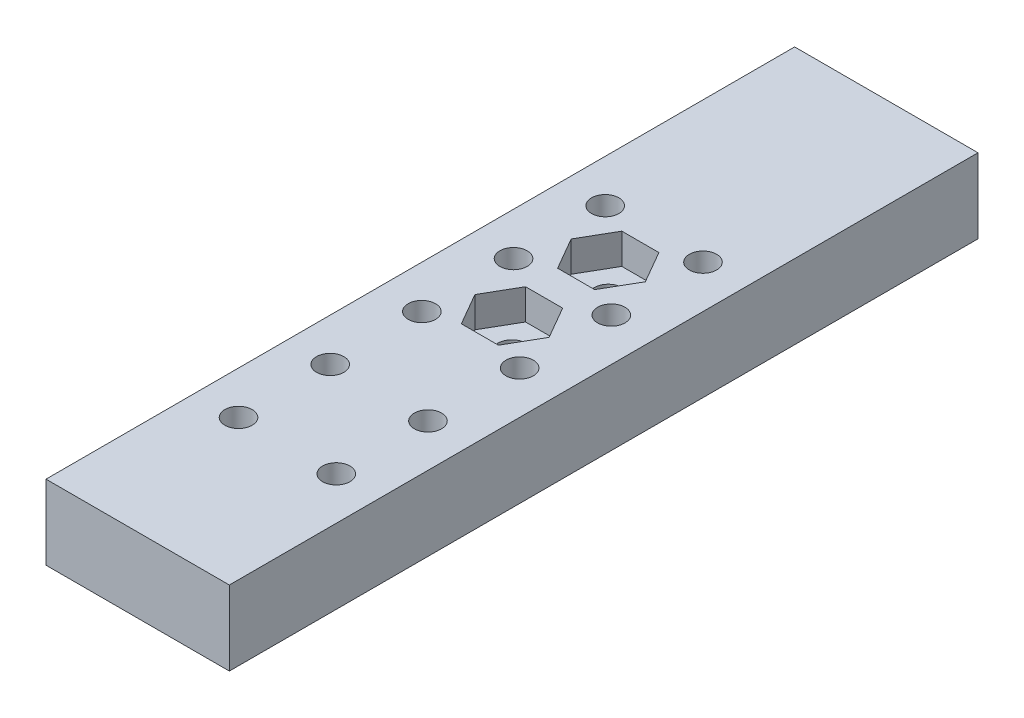
SolidWorks part; units mm, degrees
ref_plane "Front Plane" through (0, 0, 0) normal (0, 0, 1) x (1, 0, 0)
ref_plane "Top Plane" through (0, 0, 0) normal (0, 1, 0) x (1, 0, 0)
ref_plane "Right Plane" through (0, 0, 0) normal (1, 0, 0) x (0, 0, -1)
sketch "Sketch1" plane through (0, 0, 0) normal (0, 1, 0) x (1, 0, 0)
  line L0 (-8, 23.25) -> (8, 23.25) construction
  line L1 (8, 23.25) -> (0, 23.25) construction
  line L2 (0, 61.25) -> (0, -61.25) construction
  line L3 (-15, -61.25) -> (15, -61.25)
  line L4 (-15, -61.25) -> (-15, 61.25)
  line L5 (-15, 61.25) -> (15, 61.25)
  line L6 (15, -61.25) -> (15, 61.25)
  line L7 (-15, -61.25) -> (15, 61.25) construction
  line L8 (-15, 61.25) -> (15, -61.25) construction
  line L9 (-8, 23.25) -> (8, 8.25) construction
  circle A0 centre (-8, 23.25) radius 2.2349
  circle A1 centre (8, 23.25) radius 2.2349
  circle A2 centre (8, 8.25) radius 2.2349
  circle A3 centre (8, -6.75) radius 2.2349
  circle A4 centre (8, -21.75) radius 2.2349
  circle A5 centre (8, -36.75) radius 2.2349
  circle A6 centre (-8, 8.25) radius 2.2349
  circle A7 centre (-8, -6.75) radius 2.2349
  circle A8 centre (-8, -21.75) radius 2.2349
  circle A9 centre (-8, -36.75) radius 2.2349
  circle A10 centre (0, 15.75) radius 2.3
  circle A11 centre (0, 0) radius 2.3
  point P5 (0, 0)
  dimension "D3" = 4.6
  dimension "D4" = 4.6
  dimension "D1" = 122.5
  dimension "D2" = 30
extrude "Boss-Extrude1" add sketch "Sketch1" along normal blind 13
sketch "Sketch2" plane through (0, 13, 0) normal (0, 1, 0) x (1, 0, 0)
  line L0 (8, 8.25) -> (-8, 23.25) construction
  line L2 (6.0669, 0) -> (3.0335, 5.2541)
  line L3 (3.0335, 5.2541) -> (-3.0335, 5.2541)
  line L4 (-3.0335, 5.2541) -> (-6.0669, 0)
  line L5 (-6.0669, 0) -> (-3.0335, -5.2541)
  line L6 (-3.0335, -5.2541) -> (3.0335, -5.2541)
  line L7 (3.0335, -5.2541) -> (6.0669, 0)
  line L8 (6.0669, 15.75) -> (3.0335, 21.0041)
  line L9 (3.0335, 21.0041) -> (-3.0335, 21.0041)
  line L10 (-3.0335, 21.0041) -> (-6.0669, 15.75)
  line L11 (-6.0669, 15.75) -> (-3.0335, 10.4959)
  line L12 (-3.0335, 10.4959) -> (3.0335, 10.4959)
  line L13 (3.0335, 10.4959) -> (6.0669, 15.75)
  circle A0 centre (0, 0) radius 5.2541 construction
  circle A1 centre (0, 15.75) radius 5.2541 construction
extrude "Cut-Extrude1" cut sketch "Sketch2" against normal blind 5
chamfer "Chamfer1" distance 0.8 angle 45 2 edges at (15, 0, 0) (-15, 0, 0)
sketch "Sketch3" plane through (0, 0, 0) normal (0, -1, 0) x (1, 0, 0)
  circle A0 centre (8, 36.75) radius 4.5
  circle A1 centre (-8, 36.75) radius 4.5
  circle A2 centre (-8, 21.75) radius 4.5
  circle A3 centre (-8, 6.75) radius 4.5
  circle A4 centre (-8, -8.25) radius 4.5
  circle A5 centre (-8, -23.25) radius 4.5
  circle A6 centre (8, 21.75) radius 4.5
  circle A7 centre (8, 6.75) radius 4.5
  circle A8 centre (8, -8.25) radius 4.5
  circle A9 centre (8, -23.25) radius 4.5
  dimension "D1" = 9
  dimension "D2" = 2
  dimension "D3" = 5
extrude "Cut-Extrude2" cut sketch "Sketch3" against normal blind 8
chamfer "Chamfer2" distance 0.8 angle 45 2 edges at (0, 0, -61.25) (0, 0, 61.25)
